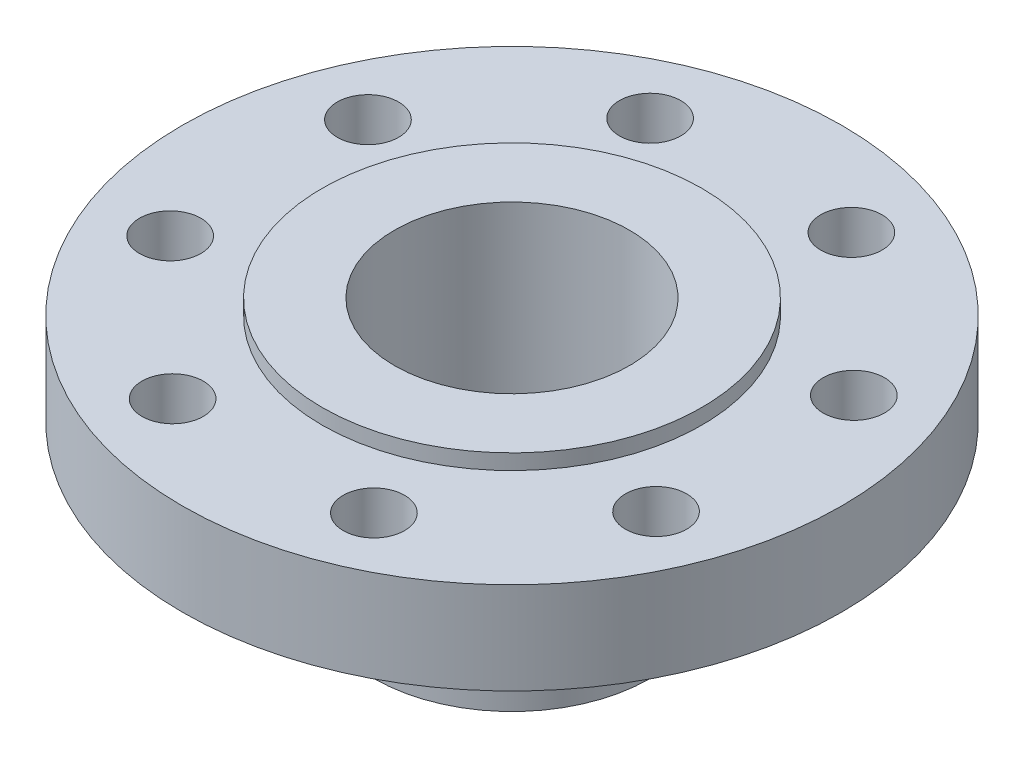
SolidWorks part; units mm, degrees
ref_plane "Front Plane" through (0, 0, 0) normal (0, 0, 1) x (1, 0, 0)
ref_plane "Top Plane" through (0, 0, 0) normal (0, 1, 0) x (1, 0, 0)
ref_plane "Right Plane" through (0, 0, 0) normal (1, 0, 0) x (0, 0, -1)
sketch "Sketch1" plane through (0, 0, 0) normal (0, 0, 1) x (1, 0, 0)
  line L0 (0, 145.4262) -> (0, -147.4014) construction
  line L1 (48.64, 0) -> (48.64, 107.95)
  line L2 (48.64, 107.95) -> (78.615, 107.95)
  line L3 (78.615, 107.95) -> (78.615, 101.6)
  line L4 (78.615, 101.6) -> (136.525, 101.6)
  line L5 (136.525, 101.6) -> (136.525, 63.5)
  line L6 (136.525, 63.5) -> (78.615, 63.5)
  line L7 (78.615, 63.5) -> (57.15, 11.29)
  line L8 (57.15, 11.29) -> (57.15, 0)
  line L9 (57.15, 0) -> (48.64, 0)
  dimension "D1" = 97.28
  dimension "D2" = 157.23
  dimension "D3" = 273.05
  dimension "D4" = 114.3
  dimension "D5" = 11.29
  dimension "D6" = 52.21
  dimension "D7" = 38.1
  dimension "D8" = 6.35
revolve "Revolve1" add sketch "Sketch1" angle 360 about L0
sketch "Sketch2" plane through (0, 101.6, 0) normal (0, 1, 0) x (1, 0, 0)
  line L0 (0, 0) -> (0, 149.6558) construction
  line L1 (0, 0) -> (-42.1794, 99.3685) construction
  line L2 (0, 0) -> (-100.0895, 40.4388) construction
  circle A0 centre (0, 0) radius 107.95 construction
  circle A1 centre (-42.1794, 99.3685) radius 12.7
  circle A2 centre (40.4388, 100.0895) radius 12.7
  circle A3 centre (99.3685, 42.1794) radius 12.7
  circle A4 centre (100.0895, -40.4388) radius 12.7
  circle A5 centre (42.1794, -99.3685) radius 12.7
  circle A6 centre (-40.4388, -100.0895) radius 12.7
  circle A7 centre (-99.3685, -42.1794) radius 12.7
  circle A8 centre (-100.0895, 40.4388) radius 12.7
  point P24 (0, 0)
  dimension "D1" = 215.9
  dimension "D2" = 25.4
  dimension "D3" = 23
  dimension "D5" = 45
  dimension "D4" = 8
extrude "Cut-Extrude1" cut sketch "Sketch2" against normal blind 53
